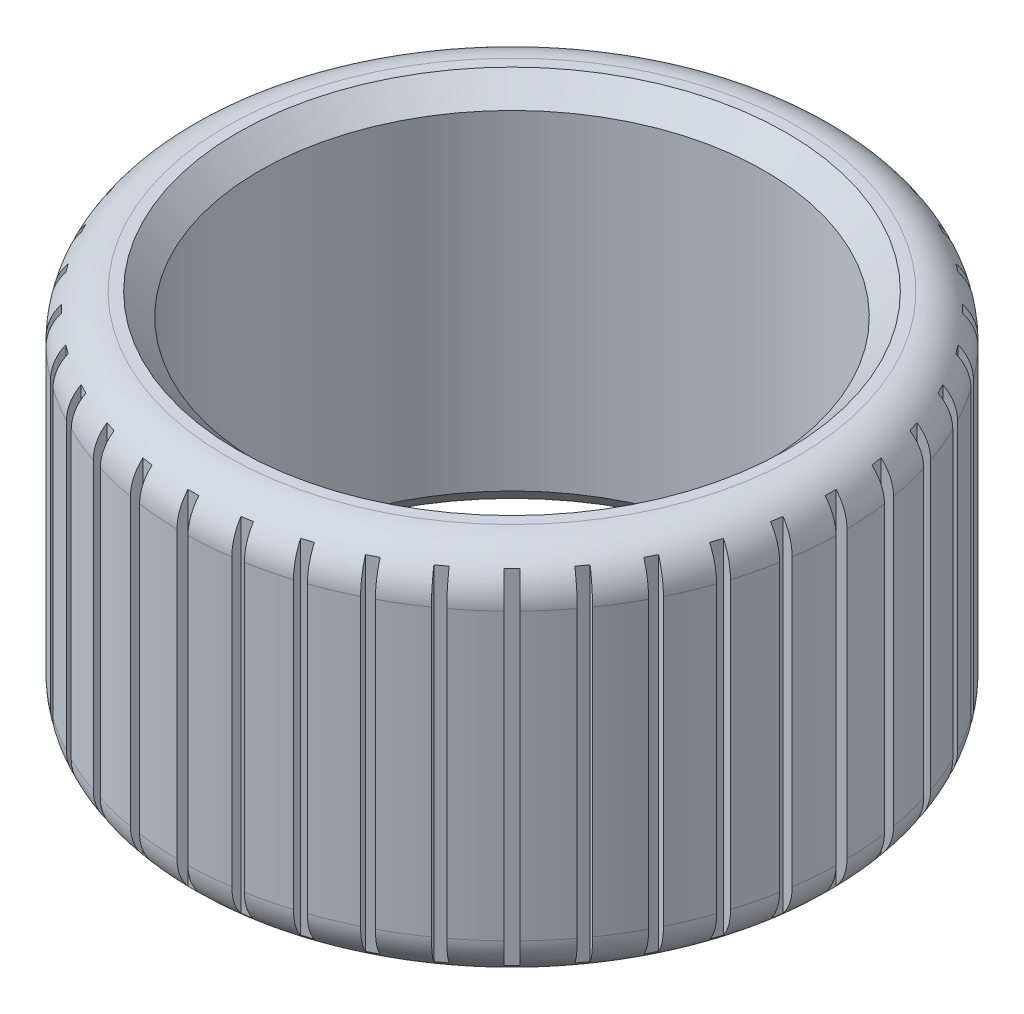
SolidWorks part; units mm, degrees
ref_plane "Front Plane" through (0, 0, 0) normal (0, 0, 1) x (1, 0, 0)
ref_plane "Top Plane" through (0, 0, 0) normal (0, 1, 0) x (1, 0, 0)
ref_plane "Right Plane" through (0, 0, 0) normal (1, 0, 0) x (0, 0, -1)
sketch "Sketch1" plane through (0, 0, 0) normal (0, 1, 0) x (1, 0, 0)
  circle A0 centre (0, 0) radius 30
  circle A1 centre (0, 0) radius 23
  dimension "D1" = 60
  dimension "D2" = 46
extrude "Boss-Extrude1" add sketch "Sketch1" along normal blind 34
chamfer "Chamfer1" distance 2 angle 45 2 edges at (0, 0, 23) (0, 34, 23)
fillet "Fillet3" radius 4 2 edges at (0, 34, 30) (0, 0, 30)
sketch "Sketch2" plane through (0, 34, 0) normal (0, 1, 0) x (1, 0, 0)
  line L0 (4.3556, 30.6966) -> (4.0428, 28.7212)
  line L1 (-0.5, 31) -> (0.5, 31)
  line L2 (-0.5, 31) -> (-0.5, 29)
  line L3 (-0.5, 29) -> (0.5, 29)
  line L4 (0.5, 31) -> (0.5, 29)
  line L5 (-0.5, 31) -> (0.5, 29) construction
  line L6 (-0.5, 29) -> (0.5, 31) construction
  line L7 (4.3556, 30.6966) -> (5.3433, 30.5401)
  line L8 (5.3433, 30.5401) -> (5.0304, 28.5647)
  line L9 (4.0428, 28.7212) -> (5.0304, 28.5647)
  line L10 (9.104, 29.6373) -> (8.486, 27.7351)
  line L11 (9.104, 29.6373) -> (10.0551, 29.3282)
  line L12 (10.0551, 29.3282) -> (9.437, 27.4261)
  line L13 (8.486, 27.7351) -> (9.437, 27.4261)
  line L14 (13.6282, 27.8482) -> (12.7202, 26.0662)
  line L15 (13.6282, 27.8482) -> (14.5192, 27.3942)
  line L16 (14.5192, 27.3942) -> (13.6112, 25.6122)
  line L17 (12.7202, 26.0662) -> (13.6112, 25.6122)
  line L18 (17.8168, 25.3734) -> (16.6413, 23.7554)
  line L19 (17.8168, 25.3734) -> (18.6259, 24.7856)
  line L20 (18.6259, 24.7856) -> (17.4503, 23.1676)
  line L21 (16.6413, 23.7554) -> (17.4503, 23.1676)
  line L22 (21.5668, 22.2739) -> (20.1525, 20.8597)
  line L23 (21.5668, 22.2739) -> (22.2739, 21.5668)
  line L24 (22.2739, 21.5668) -> (20.8597, 20.1525)
  line L25 (20.1525, 20.8597) -> (20.8597, 20.1525)
  line L26 (24.7856, 18.6259) -> (23.1676, 17.4503)
  line L27 (24.7856, 18.6259) -> (25.3734, 17.8168)
  line L28 (25.3734, 17.8168) -> (23.7554, 16.6413)
  line L29 (23.1676, 17.4503) -> (23.7554, 16.6413)
  line L30 (27.3942, 14.5192) -> (25.6122, 13.6112)
  line L31 (27.3942, 14.5192) -> (27.8482, 13.6282)
  line L32 (27.8482, 13.6282) -> (26.0662, 12.7202)
  line L33 (25.6122, 13.6112) -> (26.0662, 12.7202)
  line L34 (29.3282, 10.0551) -> (27.4261, 9.437)
  line L35 (29.3282, 10.0551) -> (29.6373, 9.104)
  line L36 (29.6373, 9.104) -> (27.7351, 8.486)
  line L37 (27.4261, 9.437) -> (27.7351, 8.486)
  line L38 (30.5401, 5.3433) -> (28.5647, 5.0304)
  line L39 (30.5401, 5.3433) -> (30.6966, 4.3556)
  line L40 (30.6966, 4.3556) -> (28.7212, 4.0428)
  line L41 (28.5647, 5.0304) -> (28.7212, 4.0428)
  line L42 (31, 0.5) -> (29, 0.5)
  line L43 (31, 0.5) -> (31, -0.5)
  line L44 (31, -0.5) -> (29, -0.5)
  line L45 (29, 0.5) -> (29, -0.5)
  line L46 (30.6966, -4.3556) -> (28.7212, -4.0428)
  line L47 (30.6966, -4.3556) -> (30.5401, -5.3433)
  line L48 (30.5401, -5.3433) -> (28.5647, -5.0304)
  line L49 (28.7212, -4.0428) -> (28.5647, -5.0304)
  line L50 (29.6373, -9.104) -> (27.7351, -8.486)
  line L51 (29.6373, -9.104) -> (29.3282, -10.0551)
  line L52 (29.3282, -10.0551) -> (27.4261, -9.437)
  line L53 (27.7351, -8.486) -> (27.4261, -9.437)
  line L54 (27.8482, -13.6282) -> (26.0662, -12.7202)
  line L55 (27.8482, -13.6282) -> (27.3942, -14.5192)
  line L56 (27.3942, -14.5192) -> (25.6122, -13.6112)
  line L57 (26.0662, -12.7202) -> (25.6122, -13.6112)
  line L58 (25.3734, -17.8168) -> (23.7554, -16.6413)
  line L59 (25.3734, -17.8168) -> (24.7856, -18.6259)
  line L60 (24.7856, -18.6259) -> (23.1676, -17.4503)
  line L61 (23.7554, -16.6413) -> (23.1676, -17.4503)
  line L62 (22.2739, -21.5668) -> (20.8597, -20.1525)
  line L63 (22.2739, -21.5668) -> (21.5668, -22.2739)
  line L64 (21.5668, -22.2739) -> (20.1525, -20.8597)
  line L65 (20.8597, -20.1525) -> (20.1525, -20.8597)
  line L66 (18.6259, -24.7856) -> (17.4503, -23.1676)
  line L67 (18.6259, -24.7856) -> (17.8168, -25.3734)
  line L68 (17.8168, -25.3734) -> (16.6413, -23.7554)
  line L69 (17.4503, -23.1676) -> (16.6413, -23.7554)
  line L70 (14.5192, -27.3942) -> (13.6112, -25.6122)
  line L71 (14.5192, -27.3942) -> (13.6282, -27.8482)
  line L72 (13.6282, -27.8482) -> (12.7202, -26.0662)
  line L73 (13.6112, -25.6122) -> (12.7202, -26.0662)
  line L74 (10.0551, -29.3282) -> (9.437, -27.4261)
  line L75 (10.0551, -29.3282) -> (9.104, -29.6373)
  line L76 (9.104, -29.6373) -> (8.486, -27.7351)
  line L77 (9.437, -27.4261) -> (8.486, -27.7351)
  line L78 (5.3433, -30.5401) -> (5.0304, -28.5647)
  line L79 (5.3433, -30.5401) -> (4.3556, -30.6966)
  line L80 (4.3556, -30.6966) -> (4.0428, -28.7212)
  line L81 (5.0304, -28.5647) -> (4.0428, -28.7212)
  line L82 (0.5, -31) -> (0.5, -29)
  line L83 (0.5, -31) -> (-0.5, -31)
  line L84 (-0.5, -31) -> (-0.5, -29)
  line L85 (0.5, -29) -> (-0.5, -29)
  line L86 (-4.3556, -30.6966) -> (-4.0428, -28.7212)
  line L87 (-4.3556, -30.6966) -> (-5.3433, -30.5401)
  line L88 (-5.3433, -30.5401) -> (-5.0304, -28.5647)
  line L89 (-4.0428, -28.7212) -> (-5.0304, -28.5647)
  line L90 (-9.104, -29.6373) -> (-8.486, -27.7351)
  line L91 (-9.104, -29.6373) -> (-10.0551, -29.3282)
  line L92 (-10.0551, -29.3282) -> (-9.437, -27.4261)
  line L93 (-8.486, -27.7351) -> (-9.437, -27.4261)
  line L94 (-13.6282, -27.8482) -> (-12.7202, -26.0662)
  line L95 (-13.6282, -27.8482) -> (-14.5192, -27.3942)
  line L96 (-14.5192, -27.3942) -> (-13.6112, -25.6122)
  line L97 (-12.7202, -26.0662) -> (-13.6112, -25.6122)
  line L98 (-17.8168, -25.3734) -> (-16.6413, -23.7554)
  line L99 (-17.8168, -25.3734) -> (-18.6259, -24.7856)
  line L100 (-18.6259, -24.7856) -> (-17.4503, -23.1676)
  line L101 (-16.6413, -23.7554) -> (-17.4503, -23.1676)
  line L102 (-21.5668, -22.2739) -> (-20.1525, -20.8597)
  line L103 (-21.5668, -22.2739) -> (-22.2739, -21.5668)
  line L104 (-22.2739, -21.5668) -> (-20.8597, -20.1525)
  line L105 (-20.1525, -20.8597) -> (-20.8597, -20.1525)
  line L106 (-24.7856, -18.6259) -> (-23.1676, -17.4503)
  line L107 (-24.7856, -18.6259) -> (-25.3734, -17.8168)
  line L108 (-25.3734, -17.8168) -> (-23.7554, -16.6413)
  line L109 (-23.1676, -17.4503) -> (-23.7554, -16.6413)
  line L110 (-27.3942, -14.5192) -> (-25.6122, -13.6112)
  line L111 (-27.3942, -14.5192) -> (-27.8482, -13.6282)
  line L112 (-27.8482, -13.6282) -> (-26.0662, -12.7202)
  line L113 (-25.6122, -13.6112) -> (-26.0662, -12.7202)
  line L114 (-29.3282, -10.0551) -> (-27.4261, -9.437)
  line L115 (-29.3282, -10.0551) -> (-29.6373, -9.104)
  line L116 (-29.6373, -9.104) -> (-27.7351, -8.486)
  line L117 (-27.4261, -9.437) -> (-27.7351, -8.486)
  line L118 (-30.5401, -5.3433) -> (-28.5647, -5.0304)
  line L119 (-30.5401, -5.3433) -> (-30.6966, -4.3556)
  line L120 (-30.6966, -4.3556) -> (-28.7212, -4.0428)
  line L121 (-28.5647, -5.0304) -> (-28.7212, -4.0428)
  line L122 (-31, -0.5) -> (-29, -0.5)
  line L123 (-31, -0.5) -> (-31, 0.5)
  line L124 (-31, 0.5) -> (-29, 0.5)
  line L125 (-29, -0.5) -> (-29, 0.5)
  line L126 (-30.6966, 4.3556) -> (-28.7212, 4.0428)
  line L127 (-30.6966, 4.3556) -> (-30.5401, 5.3433)
  line L128 (-30.5401, 5.3433) -> (-28.5647, 5.0304)
  line L129 (-28.7212, 4.0428) -> (-28.5647, 5.0304)
  line L130 (-29.6373, 9.104) -> (-27.7351, 8.486)
  line L131 (-29.6373, 9.104) -> (-29.3282, 10.0551)
  line L132 (-29.3282, 10.0551) -> (-27.4261, 9.437)
  line L133 (-27.7351, 8.486) -> (-27.4261, 9.437)
  line L134 (-27.8482, 13.6282) -> (-26.0662, 12.7202)
  line L135 (-27.8482, 13.6282) -> (-27.3942, 14.5192)
  line L136 (-27.3942, 14.5192) -> (-25.6122, 13.6112)
  line L137 (-26.0662, 12.7202) -> (-25.6122, 13.6112)
  line L138 (-25.3734, 17.8168) -> (-23.7554, 16.6413)
  line L139 (-25.3734, 17.8168) -> (-24.7856, 18.6259)
  line L140 (-24.7856, 18.6259) -> (-23.1676, 17.4503)
  line L141 (-23.7554, 16.6413) -> (-23.1676, 17.4503)
  line L142 (-22.2739, 21.5668) -> (-20.8597, 20.1525)
  line L143 (-22.2739, 21.5668) -> (-21.5668, 22.2739)
  line L144 (-21.5668, 22.2739) -> (-20.1525, 20.8597)
  line L145 (-20.8597, 20.1525) -> (-20.1525, 20.8597)
  line L146 (-18.6259, 24.7856) -> (-17.4503, 23.1676)
  line L147 (-18.6259, 24.7856) -> (-17.8168, 25.3734)
  line L148 (-17.8168, 25.3734) -> (-16.6413, 23.7554)
  line L149 (-17.4503, 23.1676) -> (-16.6413, 23.7554)
  line L150 (-14.5192, 27.3942) -> (-13.6112, 25.6122)
  line L151 (-14.5192, 27.3942) -> (-13.6282, 27.8482)
  line L152 (-13.6282, 27.8482) -> (-12.7202, 26.0662)
  line L153 (-13.6112, 25.6122) -> (-12.7202, 26.0662)
  line L154 (-10.0551, 29.3282) -> (-9.437, 27.4261)
  line L155 (-10.0551, 29.3282) -> (-9.104, 29.6373)
  line L156 (-9.104, 29.6373) -> (-8.486, 27.7351)
  line L157 (-9.437, 27.4261) -> (-8.486, 27.7351)
  line L158 (-5.3433, 30.5401) -> (-5.0304, 28.5647)
  line L159 (-5.3433, 30.5401) -> (-4.3556, 30.6966)
  line L160 (-4.3556, 30.6966) -> (-4.0428, 28.7212)
  line L161 (-5.0304, 28.5647) -> (-4.0428, 28.7212)
  circle A0 centre (0, 0) radius 30 construction
  point P0 (0, 30)
  point P166 (0, 0)
  dimension "D1" = 1
  dimension "D2" = 2
  dimension "D3" = 40
extrude "Cut-Extrude1" cut sketch "Sketch2" against normal up to surface (34 mm away) up to face at (0, 0, 26)
